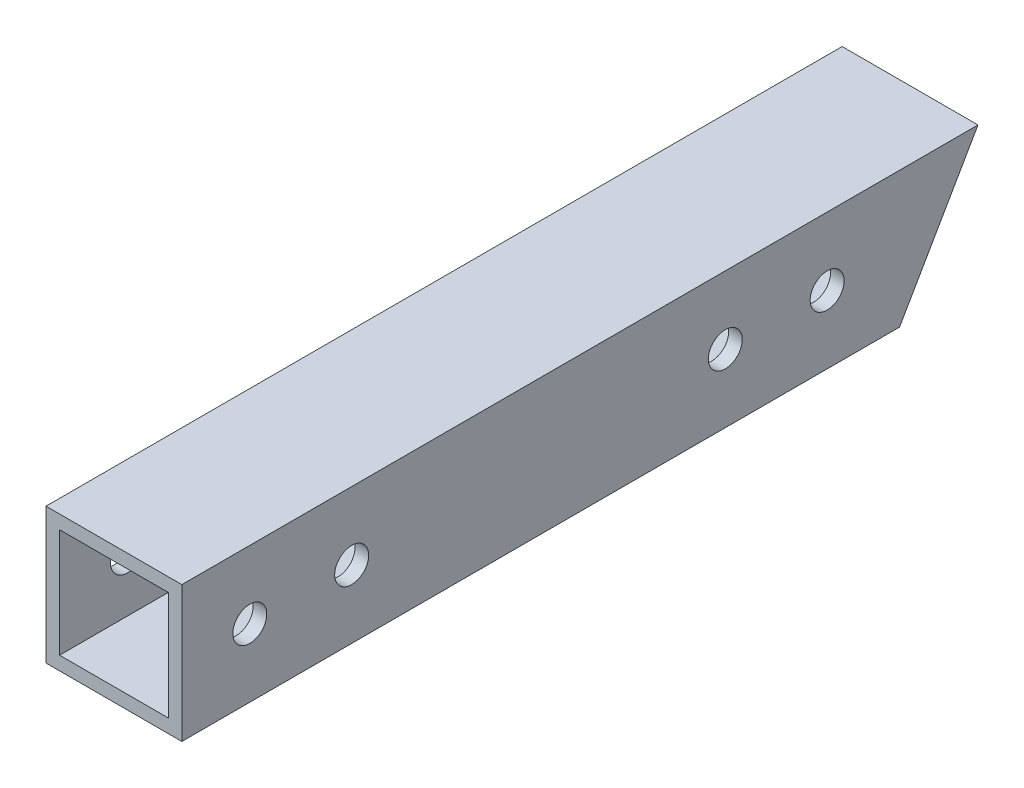
SolidWorks part; units mm, degrees
material "1345 Alloy"
ref_plane "Front Plane" through (0, 0, 0) normal (0, 0, 1) x (1, 0, 0)
ref_plane "Top Plane" through (0, 0, 0) normal (0, 1, 0) x (1, 0, 0)
ref_plane "Right Plane" through (0, 0, 0) normal (1, 0, 0) x (0, 0, -1)
sketch "Sketch1" plane through (0, 0, 0) normal (0, 0, 1) x (1, 0, 0)
  line L1 (-10, 10) -> (10, 10)
  line L2 (-10, 10) -> (-10, -10)
  line L3 (-10, -10) -> (10, -10)
  line L4 (10, 10) -> (10, -10)
  line L5 (-10, 10) -> (10, -10) construction
  line L6 (-10, -10) -> (10, 10) construction
  line L7 (-8, 8) -> (8, 8)
  line L8 (-8, 8) -> (-8, -8)
  line L9 (-8, -8) -> (8, -8)
  line L10 (8, 8) -> (8, -8)
  line L11 (-8, 8) -> (8, -8) construction
  line L12 (-8, -8) -> (8, 8) construction
  point P0 (0, 0)
  point P6 (0, 0)
  dimension "D1" = 20
  dimension "D2" = 20
  dimension "D3" = 16
extrude "Boss-Extrude1" add sketch "Sketch1" along normal blind 100
sketch "Sketch4" plane through (10, 0, 0) normal (1, 0, 0) x (0, 0, -1)
  line L0 (-136.12, 0) -> (5.2175, 0) construction
  line L1 (-100, -10) -> (-100, 10) construction
  line L2 (-50, 10) -> (-50, -10) construction
  line L3 (-100, 10) -> (0, 10) construction
  line L4 (-100, -10) -> (0, -10) construction
  circle A0 centre (-90, 0) radius 2.5
  circle A5 centre (-75, 0) radius 2.5
  circle A6 centre (-5, 0) radius 2.5
  circle A7 centre (-20, 0) radius 2.5
  dimension "D1" = 5
  dimension "D3" = 5
  dimension "D5" = 5
  dimension "D7" = 5
  dimension "D2" = 10
  dimension "D4" = 15
  dimension "D6" = 95
  dimension "D8" = 15
extrude "Cut-Extrude2" cut sketch "Sketch4" against normal through all
sketch "Sketch5" plane through (0, 0, 0) normal (0, 0, -1) x (-1, 0, 0)
  line L1 (-10, -10) -> (10, -10)
  line L2 (-10, -10) -> (-10, 10)
  line L3 (-10, 10) -> (10, 10)
  line L4 (10, -10) -> (10, 10)
  line L5 (-10, -10) -> (10, 10) construction
  line L6 (-10, 10) -> (10, -10) construction
  line L7 (-8, -8) -> (8, -8)
  line L8 (-8, -8) -> (-8, 8)
  line L9 (-8, 8) -> (8, 8)
  line L10 (8, -8) -> (8, 8)
  line L11 (-8, -8) -> (8, 8) construction
  line L12 (-8, 8) -> (8, -8) construction
  point P0 (0, 0)
  point P7 (0, 0)
extrude "Boss-Extrude2" add sketch "Sketch5" along normal blind 12.3
sketch "Sketch6" plane through (-10, 0, 0) normal (-1, 0, 0) x (0, 0, 1)
  line L0 (-12.3, 10) -> (-12.3, 1.5)
  line L1 (-12.3, -10) -> (-12.3, 10) construction
  line L2 (-12.3, 1.5) -> (-17.2075, 10)
  line L3 (-17.2075, 10) -> (-12.3, 10)
  dimension "D1" = 8.5
  dimension "D2" = 30
extrude "Boss-Extrude3" add sketch "Sketch6" against normal blind 20
sketch "Sketch7" plane through (0, 0, -12.3) normal (0, 0, 1) x (1, 0, 0)
  line L1 (-8, -8) -> (8, -8)
  line L2 (-8, -8) -> (-8, 8)
  line L3 (-8, 8) -> (8, 8)
  line L4 (8, -8) -> (8, 8)
  line L5 (-8, -8) -> (8, 8) construction
  line L6 (-8, 8) -> (8, -8) construction
  point P0 (0, 0)
extrude "Cut-Extrude3" cut sketch "Sketch7" against normal through all
sketch "Sketch8" plane through (-10, 0, 0) normal (-1, 0, 0) x (0, 0, 1)
  line L0 (-17.2075, 10) -> (-5.6605, -10)
  line L1 (100, -10) -> (-12.3, -10) construction
  line L2 (-17.2075, 10) -> (-12.3, 1.5) construction
  line L3 (-5.6605, -10) -> (-17.2075, -10)
  line L4 (-17.2075, -10) -> (-17.2075, 10)
extrude "Cut-Extrude4" cut sketch "Sketch8" against normal through all
